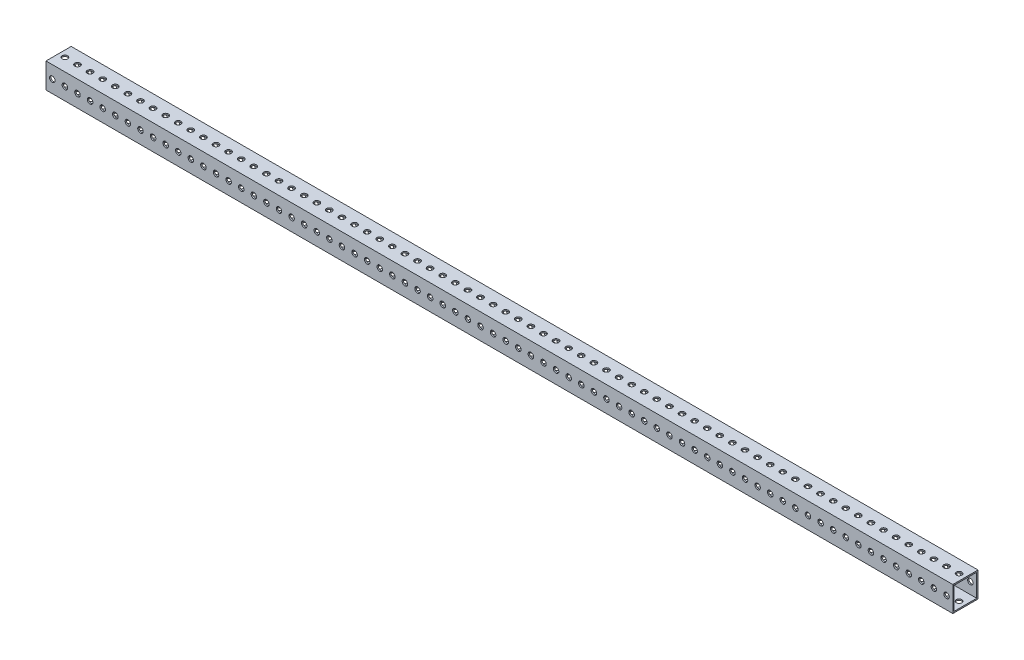
SolidWorks part; units mm, degrees
ref_plane "Front Plane" through (0, 0, 0) normal (0, 0, 1) x (1, 0, 0)
ref_plane "Top Plane" through (0, 0, 0) normal (0, 1, 0) x (1, 0, 0)
ref_plane "Right Plane" through (0, 0, 0) normal (1, 0, 0) x (0, 0, -1)
sketch "Sketch1" plane through (0, 0, 0) normal (1, 0, 0) x (0, 0, -1)
  line L1 (0, 0) -> (-50.8, 0)
  line L2 (0, 0) -> (0, 50.8)
  line L3 (0, 50.8) -> (-50.8, 50.8)
  line L4 (-50.8, 0) -> (-50.8, 50.8)
  dimension "Wd." = 50.8
  dimension "Ht." = 50.8
extrude "Extrude-Thin1" add sketch "Sketch1" along normal mid plane 1828.8 thin
sketch "Sketch2" plane through (0, 0, 0) normal (0, 0, 1) x (1, 0, 0)
  line L0 (-901.7, 25.4) -> (-927.1, 25.4) construction
  line L1 (-914.4, 50.8) -> (-914.4, 0) construction
  line L2 (-901.7, 25.4) -> (-876.3, 25.4) construction
  circle A0 centre (-901.7, 25.4) radius 5.5562
  point P2 (-914.4, 25.4)
extrude "Cut-Extrude1" cut sketch "Sketch2" along normal through all
pattern_linear "LPattern1" count 72 spacing 25.4 along (1, 0, 0) of "Cut-Extrude1"
ref_plane "Plane1" through (0, 0, 0) normal (0, -0.7071, 0.7071) x (1, 0, 0)
mirror "Mirror1" about plane through (0, 0, 0) normal (0, -0.7071, 0.7071) of "LPattern1", "Cut-Extrude1"
equation "\"D3@LPattern1\" = \"Hole Center@Sketch2\""
equation "\"D1@LPattern1\" = \"Length@Extrude-Thin1\" / \"D3@LPattern1\" "
